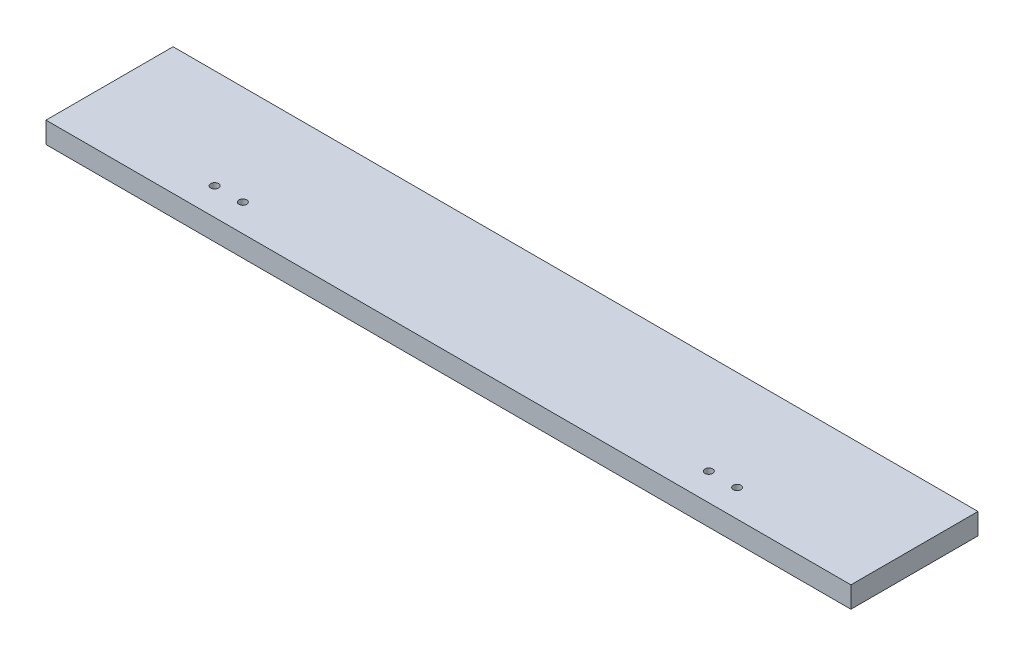
SolidWorks part; units mm, degrees
ref_plane "Front Plane" through (0, 0, 0) normal (0, 0, 1) x (1, 0, 0)
ref_plane "Top Plane" through (0, 0, 0) normal (0, 1, 0) x (1, 0, 0)
ref_plane "Right Plane" through (0, 0, 0) normal (1, 0, 0) x (0, 0, -1)
sketch "Sketch2" plane through (0, 0, 0) normal (0, 1, 0) x (1, 0, 0)
  line L1 (-361.95, -57.15) -> (361.95, -57.15)
  line L2 (-361.95, -57.15) -> (-361.95, 57.15)
  line L3 (-361.95, 57.15) -> (361.95, 57.15)
  line L4 (361.95, -57.15) -> (361.95, 57.15)
  line L5 (-361.95, -57.15) -> (361.95, 57.15) construction
  line L6 (-361.95, 57.15) -> (361.95, -57.15) construction
  point P0 (0, 0)
  dimension "D1" = 723.9
  dimension "D2" = 114.3
extrude "Boss-Extrude3" add sketch "Sketch2" along normal blind 19.05
ref_plane "Plane1" through (0, 0, 0) normal (1, 0, 0) x (0, 0, -1)
ref_plane "Plane2" through (0, 0, 0) normal (0, 0, 1) x (1, 0, 0)
sketch "Sketch3" plane through (0, 0, 0) normal (0, -1, 0) x (1, 0, 0)
  line L0 (-361.95, 57.15) -> (361.95, 57.15) construction
  line L1 (361.95, 57.15) -> (361.95, -57.15) construction
  line L2 (-361.95, -57.15) -> (-361.95, 57.15) construction
  circle A0 centre (-234.95, 32.512) radius 3.4925
  circle A1 centre (-209.55, 32.512) radius 3.4925
  circle A2 centre (209.55, 32.512) radius 3.4925
  circle A3 centre (234.95, 32.512) radius 3.4925
  point P4 (-312.1594, 22.9334)
  point P5 (-289.2746, 22.9334)
  point P6 (0, 0)
  dimension "D1" = 6.985
  dimension "D2" = 6.985
  dimension "D3" = 6.985
  dimension "D4" = 6.985
  dimension "D5" = 25.4
  dimension "D6" = 25.4
  dimension "D7" = 127
  dimension "D8" = 24.638
  dimension "D9" = 127
  dimension "D10" = 24.638
  dimension "D11" = 24.638
  dimension "D12" = 24.638
extrude "Cut-Extrude1" cut sketch "Sketch3" against normal through all both
